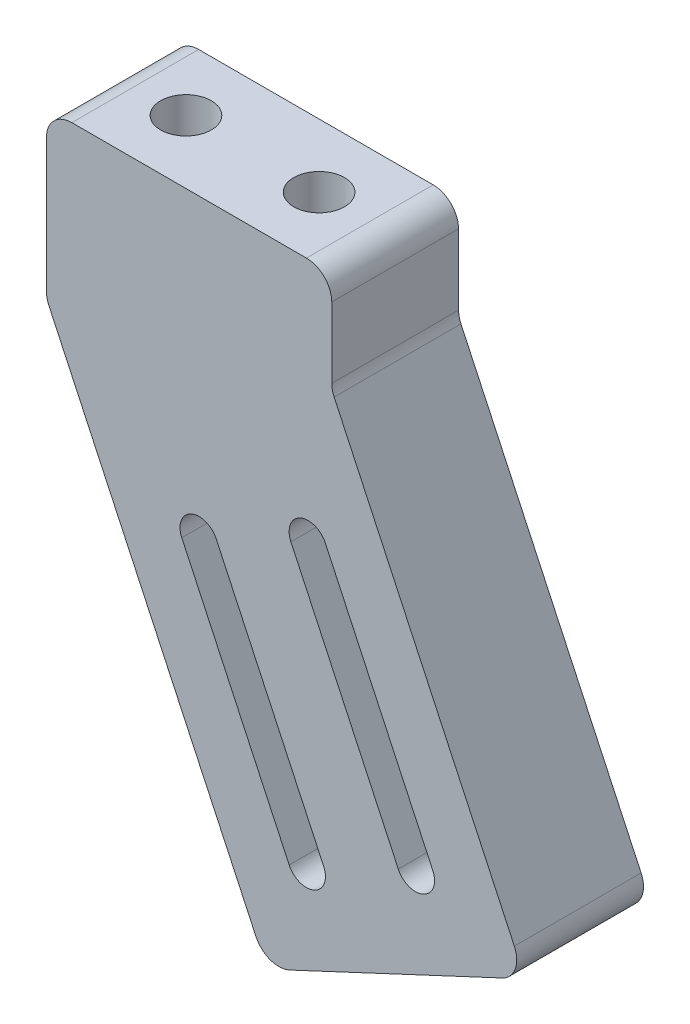
SolidWorks part; units mm, degrees
ref_plane "Front Plane" through (0, 0, 0) normal (0, 0, 1) x (1, 0, 0)
ref_plane "Top Plane" through (0, 0, 0) normal (0, 1, 0) x (1, 0, 0)
ref_plane "Right Plane" through (0, 0, 0) normal (1, 0, 0) x (0, 0, -1)
sketch "Sketch1" plane through (0, 0, 0) normal (0, 0, 1) x (1, 0, 0)
  line L0 (0, 0) -> (22.5, 0)
  line L1 (22.5, 0) -> (22.5, -8)
  line L2 (22.5, -8) -> (37.7471, -40.6118)
  line L3 (37.7471, -40.6118) -> (17.3647, -50.1412)
  line L4 (17.3647, -50.1412) -> (0, -13)
  line L5 (0, -13) -> (0, 0)
  line L7 (12.0294, -23.3824) -> (20.5, -41.5) construction
  line L8 (20.5, -41.5) -> (29.1059, -37.4765) construction
  line L9 (29.1059, -37.4765) -> (20.6353, -19.3588) construction
  line L10 (20.6353, -19.3588) -> (12.0294, -23.3824) construction
  line L11 (24.8029, -39.4882) -> (27.5559, -45.3765) construction
  line L12 (12.0294, -23.3824) -> (20.5, -41.5) construction
  line L13 (13.3882, -22.7471) -> (21.8588, -40.8647)
  line L14 (10.6706, -24.0176) -> (19.1412, -42.1353)
  line L15 (20.6353, -19.3588) -> (29.1059, -37.4765) construction
  line L16 (21.9941, -18.7235) -> (30.4647, -36.8412)
  line L17 (19.2765, -19.9941) -> (27.7471, -38.1118)
  arc A0 (13.3882, -22.7471) -> (10.6706, -24.0176) centre (12.0294, -23.3824) ccw
  arc A1 (19.1412, -42.1353) -> (21.8588, -40.8647) centre (20.5, -41.5) ccw
  arc A2 (21.9941, -18.7235) -> (19.2765, -19.9941) centre (20.6353, -19.3588) ccw
  arc A3 (27.7471, -38.1118) -> (30.4647, -36.8412) centre (29.1059, -37.4765) ccw
  point P14 (16.2647, -32.4412)
  point P19 (24.8706, -28.4176)
  dimension "D9" = 1.5
  dimension "D1" = 13
  dimension "D2" = 41
  dimension "D3" = 22.5
  dimension "D4" = 36
  dimension "D5" = 8
  dimension "D6" = 20
  dimension "D7" = 9.5
  dimension "D8" = 6.5
extrude "Boss-Extrude1" add sketch "Sketch1" along normal blind 10
hole_wizard "Ø4.0 (4) Diameter Hole1" positions "Sketch4" profile "Sketch5" hole size "Ø4.0" standard "ANSI Metric"
sketch "Sketch4" plane through (0, 0, 0) normal (0, 1, 0) x (1, 0, 0)
  line L0 (6, -5) -> (16.5, -5) construction
  line L2 (0, 0) -> (0, -10) construction
  line L4 (6, -5) -> (0, -5) construction
  point P0 (6, -5)
  point P2 (16.5, -5)
  dimension "D1" = 10.5
  dimension "D2" = 6
sketch "Sketch5" plane through (6, 0, 5) normal (1, 0, 0) x (0, 0, 1)
  line L0 (0, 0) -> (0, 16.2017)
  line L1 (0, 16.2017) -> (2, 15)
  line L2 (2, 15) -> (2, 0)
  line L5 (2, 0) -> (0, 0)
  line L10 (0, 16.2017) -> (-2, 15) construction
  line L11 (0, -6.35) -> (0, 107.95) construction
  dimension "Hole Dia." = 4
  dimension "Hole Depth" = 15
  dimension "Drill Angle" = 118
sketch "Sketch6" plane through (0, 0, 0) normal (0, 0, 1) x (1, 0, 0)
  line L0 (6, -16.2017) -> (6, 0) construction
  line L1 (2.25, -5) -> (9.75, -5)
  line L2 (2.25, -5) -> (2.25, -7.7)
  line L3 (2.25, -7.7) -> (9.75, -7.7)
  line L4 (9.75, -5) -> (9.75, -7.7)
  line L5 (2.25, -5) -> (9.75, -7.7) construction
  line L6 (2.25, -7.7) -> (9.75, -5) construction
  line L7 (12.75, -5) -> (20.25, -5)
  line L8 (12.75, -5) -> (12.75, -7.7)
  line L9 (12.75, -7.7) -> (20.25, -7.7)
  line L10 (20.25, -5) -> (20.25, -7.7)
  line L11 (12.75, -5) -> (20.25, -7.7) construction
  line L12 (12.75, -7.7) -> (20.25, -5) construction
  line L13 (16.5, -16.2017) -> (16.5, 0) construction
  line L14 (22.5, 0) -> (0, 0) construction
  point P0 (6, -6.35)
  point P5 (16.5, -6.35)
  dimension "D1" = 5
  dimension "D2" = 7.5
  dimension "D3" = 2.7
extrude "Cut-Extrude1" cut sketch "Sketch6" along normal blind 8.75
fillet "Fillet1" radius 2 6 edges at (0, 0, 5) (0, -13, 5) (17.3647, -50.1412, 5) (37.7471, -40.6118, 5) (22.5, -8, 5) (22.5, 0, 5)
equation "\"d\"= 10"
equation "\"D1@Boss-Extrude1\"=\"d\""
equation "\"D1@Cut-Extrude1\"=\"d\"/2+3.75"
